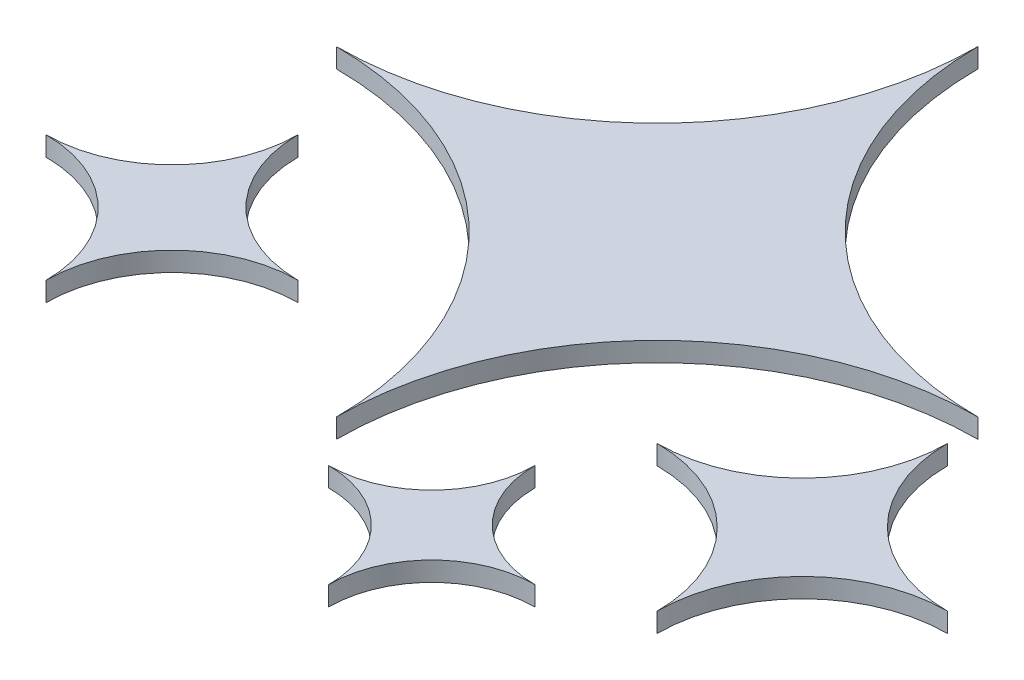
SolidWorks part; units mm, degrees
ref_plane "Front Plane" through (0, 0, 0) normal (0, 0, 1) x (1, 0, 0)
ref_plane "Top Plane" through (0, 0, 0) normal (0, 1, 0) x (1, 0, 0)
ref_plane "Right Plane" through (0, 0, 0) normal (1, 0, 0) x (0, 0, -1)
sketch "Sketch1" plane through (0, 0, 0) normal (0, 1, 0) x (1, 0, 0)
  line L0 (19.2166, 52.5253) -> (96.0829, 52.5253) construction
  line L1 (67, 113.5) -> (67, 71.5) construction
  line L2 (67, 71.5) -> (25, 71.5) construction
  line L3 (25, 113.5) -> (109, 29.5) construction
  line L4 (109, 113.5) -> (25, 29.5) construction
  line L5 (25, 63.1063) -> (25, 79.8937) construction
  line L6 (110, 66.5) -> (110, 47.5) construction
  line L7 (110, 47.5) -> (91, 47.5) construction
  line L8 (91, 66.5) -> (129, 28.5) construction
  line L9 (129, 66.5) -> (91, 28.5) construction
  line L10 (85.5, 37) -> (85.5, 23.5) construction
  line L11 (85.5, 23.5) -> (72, 23.5) construction
  line L12 (72, 37) -> (99, 10) construction
  line L13 (99, 37) -> (72, 10) construction
  line L14 (32.5, 59) -> (32.5, 42.5) construction
  line L15 (32.5, 42.5) -> (16, 42.5) construction
  line L16 (16, 59) -> (49, 26) construction
  line L17 (49, 59) -> (16, 26) construction
  line L18 (16, 42) -> (16, 43) construction
  line L19 (129, 47) -> (129, 48) construction
  line L21 (72, 24) -> (72, 23) construction
  arc A0 (67, 113.5) -> (25, 71.5) centre (25, 113.5) cw
  arc A1 (67, 113.5) -> (109, 71.5) centre (109, 113.5) ccw
  arc A2 (67, 29.5) -> (109, 71.5) centre (109, 29.5) cw
  arc A3 (67, 29.5) -> (25, 71.5) centre (25, 29.5) ccw
  arc A4 (110, 66.5) -> (91, 47.5) centre (91, 66.5) cw
  arc A5 (110, 66.5) -> (129, 47.5) centre (129, 66.5) ccw
  arc A6 (110, 28.5) -> (129, 47.5) centre (129, 28.5) cw
  arc A7 (110, 28.5) -> (91, 47.5) centre (91, 28.5) ccw
  arc A8 (85.5, 37) -> (72, 23.5) centre (72, 37) cw
  arc A9 (85.5, 37) -> (99, 23.5) centre (99, 37) ccw
  arc A10 (85.5, 10) -> (99, 23.5) centre (99, 10) cw
  arc A11 (85.5, 10) -> (72, 23.5) centre (72, 10) ccw
  arc A12 (32.5, 59) -> (16, 42.5) centre (16, 59) cw
  arc A13 (32.5, 59) -> (49, 42.5) centre (49, 59) ccw
  arc A14 (32.5, 26) -> (49, 42.5) centre (49, 26) cw
  arc A15 (32.5, 26) -> (16, 42.5) centre (16, 26) ccw
  point P2 (67, 71.5)
  point P9 (25, 79.8937)
  point P14 (25, 63.1063)
  point P16 (25, 71.5)
  point P17 (109, 71.5)
  point P18 (16, 42)
  point P19 (16, 43)
  point P21 (110, 47.5)
  point P32 (16, 42.5)
  point P33 (49, 42)
  point P34 (49, 42.5)
  point P35 (72, 24)
  point P36 (129, 47)
  point P37 (129, 48)
  point P40 (129, 47.5)
  point P43 (85.5, 23.5)
  point P53 (32.5, 42.5)
  point P63 (72, 23)
  point P64 (72, 23.5)
  point P65 (99, 23.5)
  point P66 (99, 23.5)
  point P67 (91, 47.5)
  point P68 (0, 0)
  point P69 (0, 0)
  point P70 (0, 0)
  point P71 (0, 0)
extrude "Boss-Extrude1" add sketch "Sketch1" along normal blind 2.54
